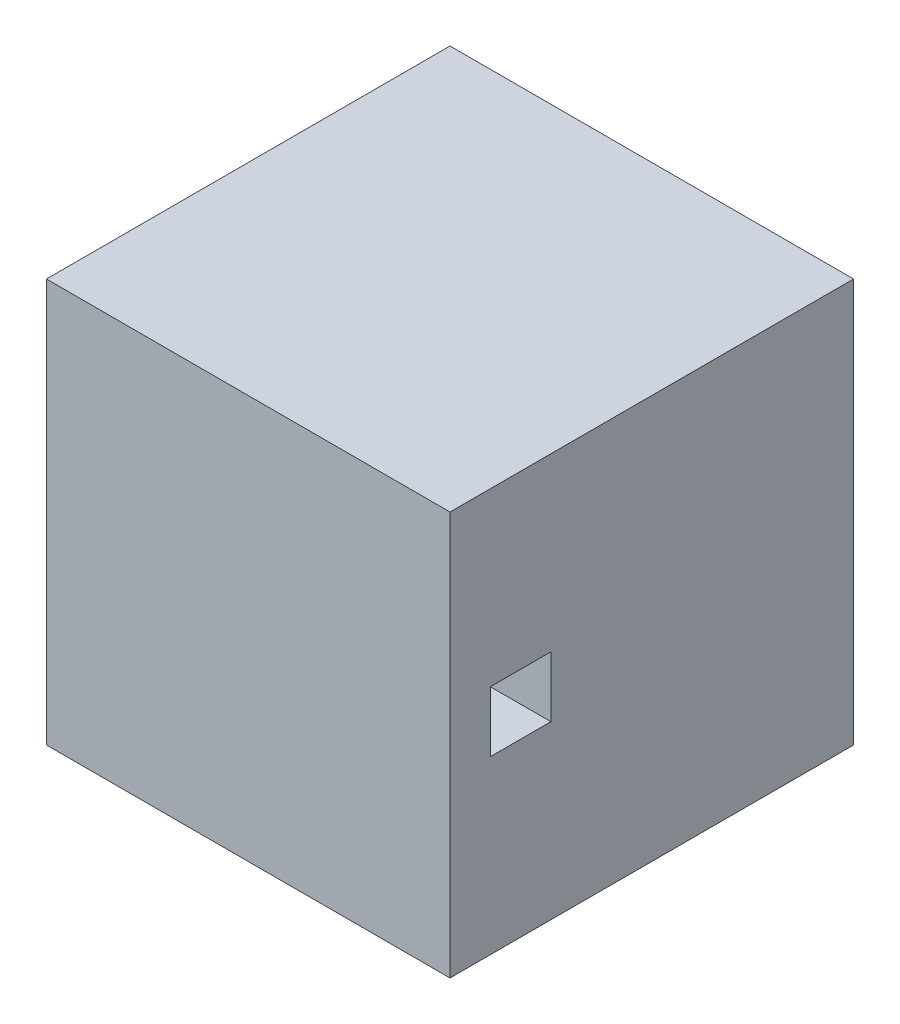
SolidWorks part; units mm, degrees
ref_plane "Front Plane" through (0, 0, 0) normal (0, 0, 1) x (1, 0, 0)
ref_plane "Top Plane" through (0, 0, 0) normal (0, 1, 0) x (1, 0, 0)
ref_plane "Right Plane" through (0, 0, 0) normal (1, 0, 0) x (0, 0, -1)
sketch "Sketch1" plane through (0, 0, 0) normal (0, 0, 1) x (1, 0, 0)
  line L1 (12.7, -12.7) -> (-12.7, -12.7)
  line L2 (12.7, -12.7) -> (12.7, 12.7)
  line L3 (12.7, 12.7) -> (-12.7, 12.7)
  line L4 (-12.7, -12.7) -> (-12.7, 12.7)
  line L5 (12.7, -12.7) -> (-12.7, 12.7) construction
  line L6 (12.7, 12.7) -> (-12.7, -12.7) construction
  point P0 (0, 0)
  dimension "D1" = 25.4
  dimension "D2" = 25.4
extrude "Boss-Extrude1" add sketch "Sketch1" along normal blind 25.4
sketch "Sketch2" plane through (0, 0, 0) normal (0, 0, -1) x (-1, 0, 0)
  line L5 (-12.7, 0) -> (12.7, 0) construction
  line L6 (-12.7, -12.7) -> (-12.7, 12.7) construction
  line L7 (12.7, 12.7) -> (12.7, -12.7) construction
  line L8 (-1.27, -3.81) -> (11.43, -3.81)
  line L9 (-1.27, -3.81) -> (-1.27, 3.81)
  line L10 (-1.27, 3.81) -> (11.43, 3.81)
  line L11 (11.43, -3.81) -> (11.43, 3.81)
  line L12 (-1.27, -3.81) -> (11.43, 3.81) construction
  line L13 (-1.27, 3.81) -> (11.43, -3.81) construction
  point P0 (0, 0)
  point P8 (5.08, 0)
  dimension "D1" = 1.27
  dimension "D2" = 7.62
  dimension "D3" = 12.7
extrude "Cut-Extrude1" cut sketch "Sketch2" against normal blind 22.86
sketch "Sketch3" plane through (12.7, 0, 0) normal (1, 0, 0) x (0, 0, -1)
  line L0 (-25.4, 0) -> (0, 0) construction
  line L1 (-25.4, -12.7) -> (-25.4, 12.7) construction
  line L2 (0, -12.7) -> (0, 12.7) construction
  line L4 (-19.05, 1.905) -> (-22.86, 1.905)
  line L5 (-19.05, 1.905) -> (-19.05, -1.905)
  line L6 (-19.05, -1.905) -> (-22.86, -1.905)
  line L7 (-22.86, 1.905) -> (-22.86, -1.905)
  line L8 (-19.05, 1.905) -> (-22.86, -1.905) construction
  line L9 (-19.05, -1.905) -> (-22.86, 1.905) construction
  point P6 (-20.955, 0)
  dimension "D1" = 2.54
  dimension "D2" = 3.81
  dimension "D3" = 3.81
extrude "Cut-Extrude2" cut sketch "Sketch3" against normal blind 22.86
